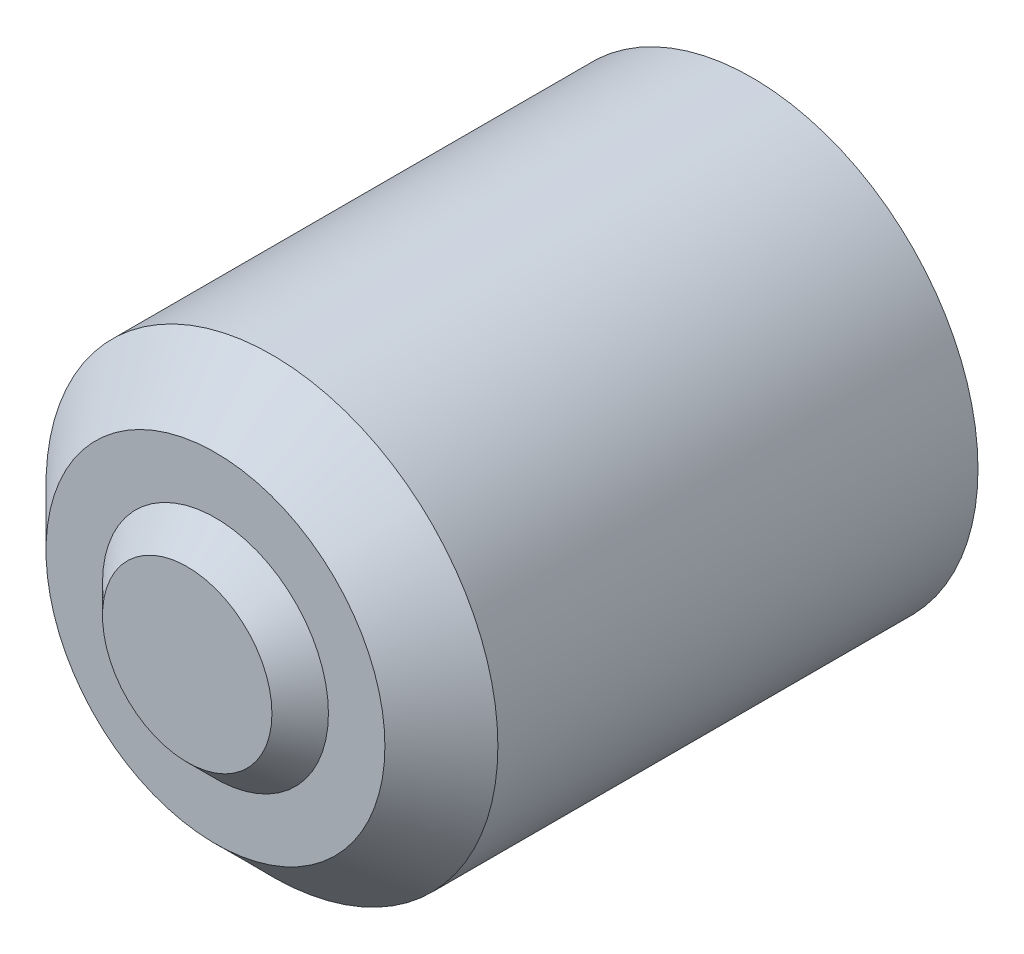
SolidWorks part; units mm, degrees
ref_plane "Front Plane" through (0, 0, 0) normal (0, 0, 1) x (1, 0, 0)
ref_plane "Top Plane" through (0, 0, 0) normal (0, 1, 0) x (1, 0, 0)
ref_plane "Right Plane" through (0, 0, 0) normal (1, 0, 0) x (0, 0, -1)
sketch "Sketch1" plane through (0, 0, 0) normal (0, 1, 0) x (1, 0, 0)
  line L0 (12, 30) -> (0, 30)
  line L1 (0, 30) -> (0, 0)
  line L2 (0, 0) -> (4.5, 0)
  line L3 (4.5, 0) -> (6, 1.5)
  line L4 (6, 1.5) -> (9, 1.5)
  line L5 (9, 1.5) -> (12, 4.5)
  line L6 (12, 4.5) -> (12, 30)
  line L7 (0, 30) -> (0, 0) construction
revolve "Revolve1" add sketch "Sketch1" angle 360 about L7
